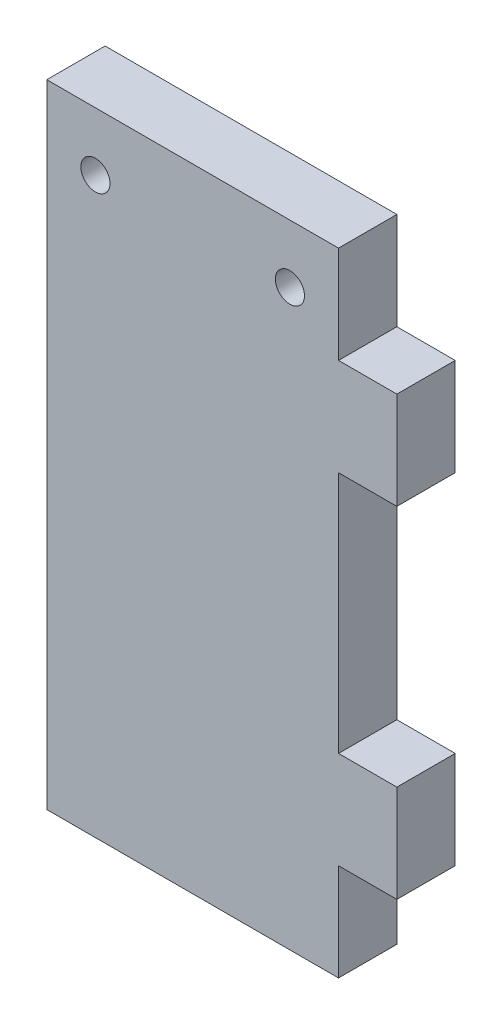
SolidWorks part; units mm, degrees
ref_plane "Plan de face" through (0, 0, 0) normal (0, 0, 1) x (1, 0, 0)
ref_plane "Plan de dessus" through (0, 0, 0) normal (0, 1, 0) x (1, 0, 0)
ref_plane "Plan de droite" through (0, 0, 0) normal (1, 0, 0) x (0, 0, -1)
sketch "Esquisse1" plane through (0, 0, 0) normal (0, 0, 1) x (1, 0, 0)
  line L1 (0, 0) -> (-30, 0)
  line L2 (0, 0) -> (0, 65)
  line L3 (0, 65) -> (-30, 65)
  line L4 (-30, 0) -> (-30, 65)
  dimension "D1" = 65
  dimension "D2" = 30
extrude "Boss.-Extru.1" add sketch "Esquisse1" along normal blind 6
sketch "Esquisse2" plane through (0, 0, 0) normal (1, 0, 0) x (0, 0, -1)
  line L0 (-6, 0) -> (-6, 65) construction
  line L1 (-6, 20) -> (0, 20)
  line L2 (-6, 20) -> (-6, 10)
  line L3 (-6, 10) -> (0, 10)
  line L4 (0, 20) -> (0, 10)
  line L5 (0, 0) -> (0, 65) construction
  line L6 (-6, 0) -> (0, 0) construction
  line L7 (-6, 65) -> (0, 65) construction
  line L8 (-6, 55) -> (0, 55)
  line L9 (-6, 55) -> (-6, 45)
  line L10 (-6, 45) -> (0, 45)
  line L11 (0, 55) -> (0, 45)
  point P14 (-3, 65)
  dimension "D1" = 10
  dimension "D2" = 10
  dimension "D3" = 10
  dimension "D4" = 10
extrude "Boss.-Extru.3" add sketch "Esquisse2" along normal blind 6
sketch "Esquisse3" plane through (0, 0, 6) normal (0, 0, 1) x (1, 0, 0)
  line L0 (-30, 65) -> (-30, 0) construction
  line L1 (0, 65) -> (-30, 65) construction
  circle A0 centre (-25, 59) radius 1.5
  circle A1 centre (-5, 59) radius 1.5
  dimension "D1" = 20
  dimension "D5" = 3
  dimension "D6" = 3
  dimension "D2" = 5
  dimension "D3" = 6
  dimension "D4" = 0
extrude "Enlèv. mat.-Extru.1" cut sketch "Esquisse3" against normal blind 6
